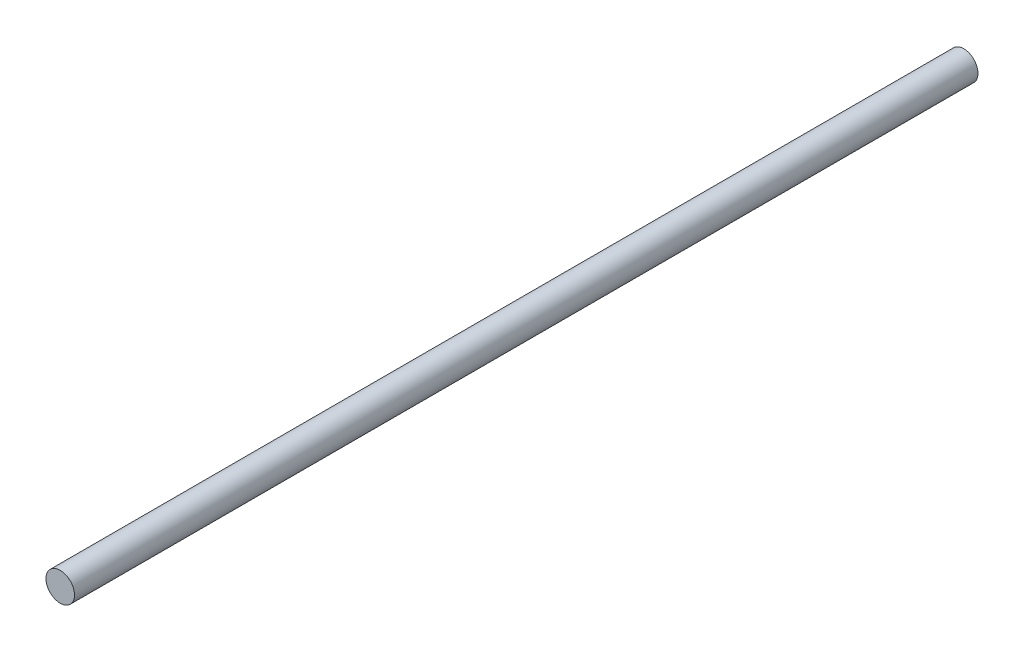
SolidWorks part; units mm, degrees
ref_plane "前视基准面" through (0, 0, 0) normal (0, 0, 1) x (1, 0, 0)
ref_plane "上视基准面" through (0, 0, 0) normal (0, 1, 0) x (1, 0, 0)
ref_plane "右视基准面" through (0, 0, 0) normal (1, 0, 0) x (0, 0, -1)
sketch "草图1" plane through (0, 0, 0) normal (0, 0, 1) x (1, 0, 0)
  circle A0 centre (0, 0) radius 3
  dimension "D1" = 6
extrude "凸台-拉伸1" add sketch "草图1" along normal blind 190
